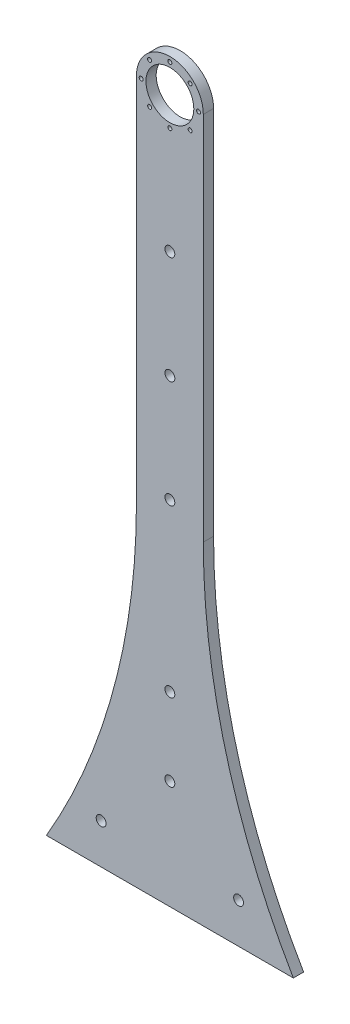
SolidWorks part; units mm, degrees
ref_plane "Front Plane" through (0, 0, 0) normal (0, 0, 1) x (1, 0, 0)
ref_plane "Top Plane" through (0, 0, 0) normal (0, 1, 0) x (1, 0, 0)
ref_plane "Right Plane" through (0, 0, 0) normal (1, 0, 0) x (0, 0, -1)
sketch "Sketch1" plane through (0, 0, 0) normal (0, 0, 1) x (1, 0, 0)
  line L0 (-112.3, 0) -> (112.3, 0) construction
  line L1 (-112.3, 0) -> (112.3, 0)
  line L2 (-29, 408.6) -> (29, 408.6) construction
  line L3 (-29, 408.6) -> (29, 408.6)
  line L4 (-31, 371.4) -> (-31, 408.6) construction
  line L5 (31, 408.6) -> (31, 371.4) construction
  line L6 (-31, 371.4) -> (-31, 408.6)
  line L7 (31, 408.6) -> (31, 371.4)
  line L8 (58.8, 370.05) -> (-58.8, 370.05) construction
  line L9 (58.8, 370.05) -> (-58.8, 370.05)
  line L10 (-125, 20) -> (125, 20) construction
  line L11 (-125, 20) -> (125, 20)
  line L12 (125, 0) -> (125, 10.5) construction
  line L13 (125, 0) -> (125, 10.5)
  line L14 (-125, 10.5) -> (-125, 0) construction
  line L15 (-125, 10.5) -> (-125, 0)
  circle A1 centre (0, 390) radius 8.5
  circle A2 centre (0, 390) radius 8.5
  circle A3 centre (0, 390) radius 3.025
  circle A4 centre (0, 390) radius 3.025
  dimension "D1" = 0
  dimension "D2" = 0
sketch "Sketch2" plane through (0, 0, 0) normal (0, 0, 1) x (1, 0, 0)
  line L0 (-65, 20) -> (65, 20)
  line L1 (-17.6, 390) -> (-17.6, 0) construction
  line L2 (-112.3, 0) -> (112.3, 0) construction
  line L3 (17.6, 390) -> (17.6, 0) construction
  line L4 (-65, 0) -> (65, 0) construction
  line L5 (-65, 0) -> (-65, 20) construction
  line L6 (-125, 20) -> (125, 20) construction
  line L7 (65, 0) -> (65, 20) construction
  line L8 (-125, 10.5) -> (-125, 0) construction
  line L9 (-17.6, 390) -> (-17.6, 195)
  line L10 (17.6, 390) -> (17.6, 195)
  arc A0 (17.6, 390) -> (-17.6, 390) centre (0, 390) ccw
  circle A1 centre (0, 390) radius 12.6 construction
  circle A3 centre (0, 390) radius 12.6
  arc A4 (17.6, 195) -> (65, 20) centre (364.3485, 195) ccw
  arc A5 (-65, 20) -> (-17.6, 195) centre (-364.3485, 195) ccw
  arc A6 (17.6, 390) -> (-17.6, 390) centre (0, 390) ccw construction
  point P3 (0, 407.6)
  point P13 (0, 0)
  point P30 (17.6, 195)
  dimension "D3" = 60
extrude "Boss-Extrude1" add sketch "Sketch2" against normal blind 5.4
sketch "Sketch3" plane through (0, 0, -5.4) normal (0, 0, -1) x (-1, 0, 0)
  circle A1 centre (10.6773, 400.6773) radius 1.05
  circle A2 centre (10.6773, 400.6773) radius 1.05
  circle A3 centre (0, 405.1) radius 1.05
  circle A4 centre (0, 405.1) radius 1.05
  circle A5 centre (-10.6773, 400.6773) radius 1.05
  circle A6 centre (-10.6773, 400.6773) radius 1.05
  circle A7 centre (-15.1, 390) radius 1.05
  circle A8 centre (-15.1, 390) radius 1.05
  circle A9 centre (-10.6773, 379.3227) radius 1.05
  circle A10 centre (-10.6773, 379.3227) radius 1.05
  circle A11 centre (0, 374.9) radius 1.05
  circle A12 centre (0, 374.9) radius 1.05
  circle A13 centre (10.6773, 379.3227) radius 1.05
  circle A14 centre (10.6773, 379.3227) radius 1.05
  circle A15 centre (15.1, 390) radius 1.05
  circle A16 centre (15.1, 390) radius 1.05
  circle A17 centre (0, 262.1) radius 2.6
  circle A18 centre (0, 262.1) radius 2.6
  circle A19 centre (0, 318.7) radius 2.6
  circle A20 centre (0, 318.7) radius 2.6
  circle A21 centre (-36.1749, 41.0875) radius 2.6
  circle A22 centre (-36.1749, 41.0875) radius 2.6
  circle A23 centre (36.1749, 41.0875) radius 2.6
  circle A24 centre (36.1749, 41.0875) radius 2.6
  circle A25 centre (0, 77.2624) radius 2.6
  circle A26 centre (0, 77.2624) radius 2.6
  circle A27 centre (0, 117.9824) radius 2.6
  circle A28 centre (0, 117.9824) radius 2.6
  circle A29 centre (0, 205.5) radius 2.6
  circle A30 centre (0, 205.5) radius 2.6
  dimension "D1" = 0
  dimension "D2" = 0
  dimension "D3" = 0
  dimension "D4" = 0
  dimension "D5" = 0
  dimension "D6" = 0
  dimension "D7" = 0
  dimension "D8" = 0
  dimension "D9" = 0
  dimension "D10" = 0
  dimension "D11" = 0
  dimension "D12" = 0
  dimension "D13" = 0
  dimension "D14" = 0
  dimension "D15" = 0
extrude "Cut-Extrude1" cut sketch "Sketch3" against normal through all
equation "\"Black_acrylic\"= 1.35mm"
equation "\"MDF_base\"= 20mm"
equation "\"Supports_material\"= 5.4mm"
equation "\"D1@Boss-Extrude1\"=\"Supports_material\""
